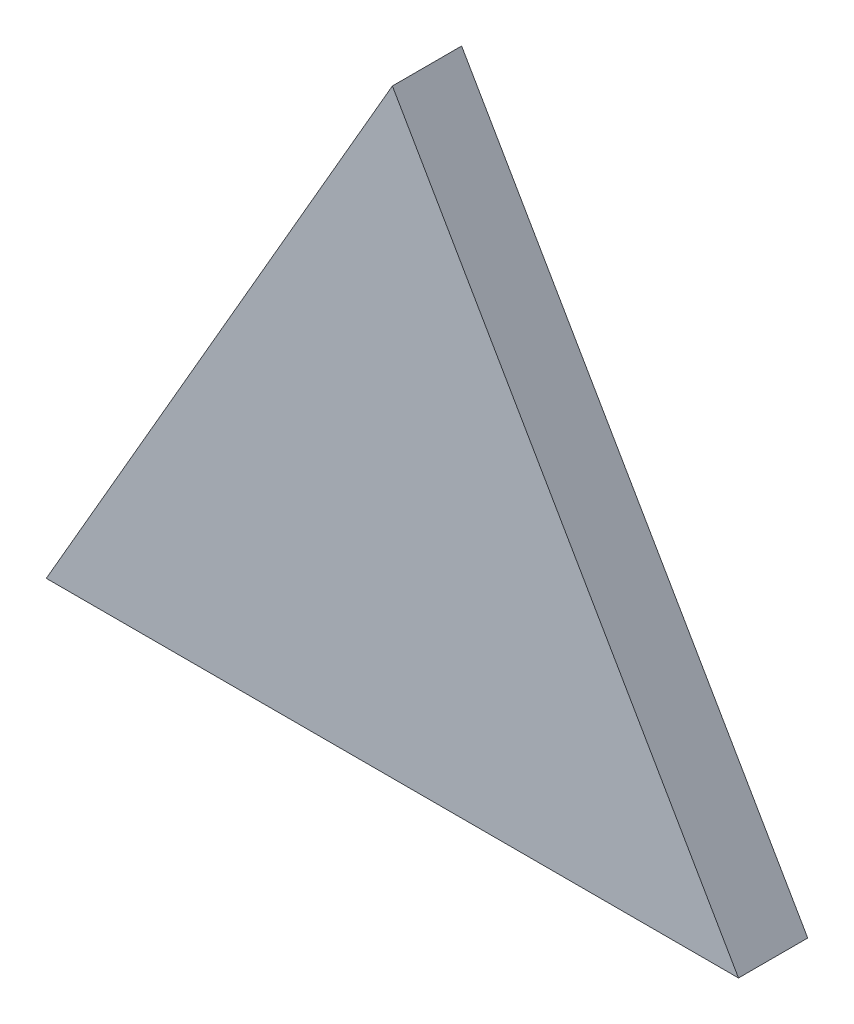
SolidWorks part; units mm, degrees
ref_plane "Front Plane" through (0, 0, 0) normal (0, 0, 1) x (1, 0, 0)
ref_plane "Top Plane" through (0, 0, 0) normal (0, 1, 0) x (1, 0, 0)
ref_plane "Right Plane" through (0, 0, 0) normal (1, 0, 0) x (0, 0, -1)
sketch "Sketch1" plane through (0, 0, 0) normal (0, 0, 1) x (1, 0, 0)
  line L0 (0, 0) -> (0, 73.3235) construction
  line L1 (0, 73.3235) -> (-63.5, -36.6617)
  line L2 (-63.5, -36.6617) -> (63.5, -36.6617)
  line L3 (63.5, -36.6617) -> (0, 73.3235)
  circle A0 centre (0, 0) radius 73.3235 construction
  dimension "D1" = 127
extrude "Boss-Extrude1" add sketch "Sketch1" along normal blind 12.7
